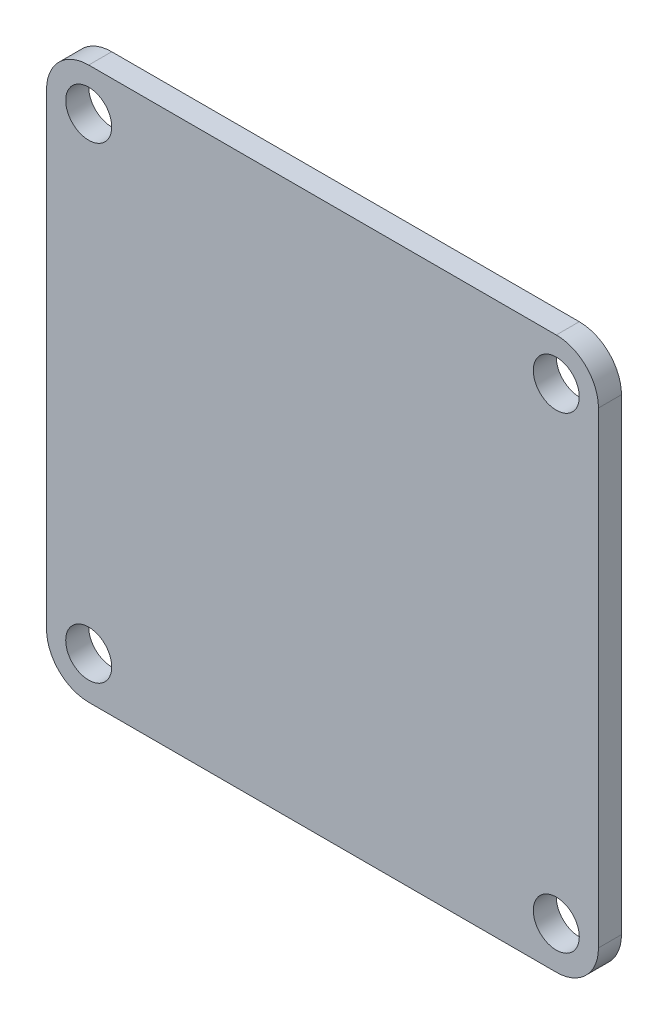
SolidWorks part; units mm, degrees
ref_plane "前视基准面" through (0, 0, 0) normal (0, 0, 1) x (1, 0, 0)
ref_plane "上视基准面" through (0, 0, 0) normal (0, 1, 0) x (1, 0, 0)
ref_plane "右视基准面" through (0, 0, 0) normal (1, 0, 0) x (0, 0, -1)
sketch "草图1" plane through (0, 0, 0) normal (0, 0, 1) x (1, 0, 0)
  line L0 (0, 18) -> (0, -18) construction
  line L1 (-15.25, 18) -> (15.25, 18)
  line L2 (-18, 15.25) -> (-18, -15.25)
  line L3 (-15.25, -18) -> (15.25, -18)
  line L4 (18, 15.25) -> (18, -15.25)
  line L5 (-18, 18) -> (18, -18) construction
  line L6 (-18, -18) -> (18, 18) construction
  line L7 (-18, 0) -> (18, 0) construction
  circle A0 centre (-15.25, 15.25) radius 1.5
  circle A1 centre (15.25, 15.25) radius 1.5
  circle A2 centre (15.25, -15.25) radius 1.5
  circle A3 centre (-15.25, -15.25) radius 1.5
  arc A4 (-15.25, -18) -> (-18, -15.25) centre (-15.25, -15.25) cw
  arc A5 (15.25, -18) -> (18, -15.25) centre (15.25, -15.25) ccw
  arc A6 (18, 15.25) -> (15.25, 18) centre (15.25, 15.25) ccw
  arc A7 (-18, 15.25) -> (-15.25, 18) centre (-15.25, 15.25) cw
  point P0 (0, 0)
  dimension "D1" = 3
  dimension "D2" = 30.5
  dimension "D5" = 2.75
  dimension "D3" = 36
  dimension "D4" = 36
extrude "凸台-拉伸1" add sketch "草图1" along normal blind 1.5
